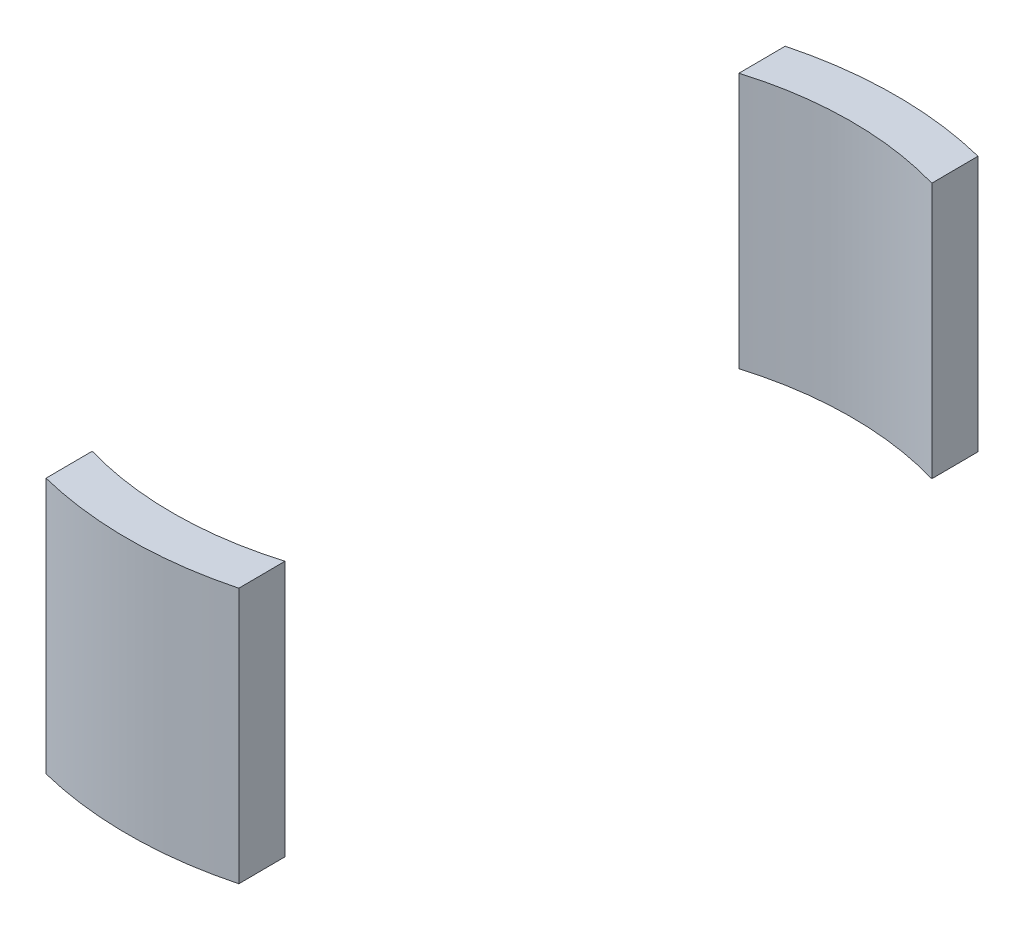
SolidWorks part; units mm, degrees
ref_plane "Front Plane" through (0, 0, 0) normal (0, 0, 1) x (1, 0, 0)
ref_plane "Top Plane" through (0, 0, 0) normal (0, 1, 0) x (1, 0, 0)
ref_plane "Right Plane" through (0, 0, 0) normal (1, 0, 0) x (0, 0, -1)
sketch "Sketch1" plane through (0, 0, 0) normal (0, 1, 0) x (1, 0, 0)
  line L1 (-0.7665, 2.9004) -> (-0.7642, 2.5374)
  line L2 (0.731, 2.9096) -> (0.7332, 2.5466)
  line L3 (-0.7332, -2.5466) -> (-0.731, -2.9096)
  line L4 (0.7642, -2.5374) -> (0.7665, -2.9004)
  arc A0 (-0.7332, -2.5466) -> (0.7642, -2.5374) centre (0, 0) ccw
  arc A1 (-0.731, -2.9096) -> (0.7665, -2.9004) centre (0, 0) ccw
  arc A2 (0.7332, 2.5466) -> (-0.7642, 2.5374) centre (0, 0) ccw
  arc A3 (0.731, 2.9096) -> (-0.7665, 2.9004) centre (0, 0) ccw
extrude "Boss-Extrude1" add sketch "Sketch1" along normal blind 2
